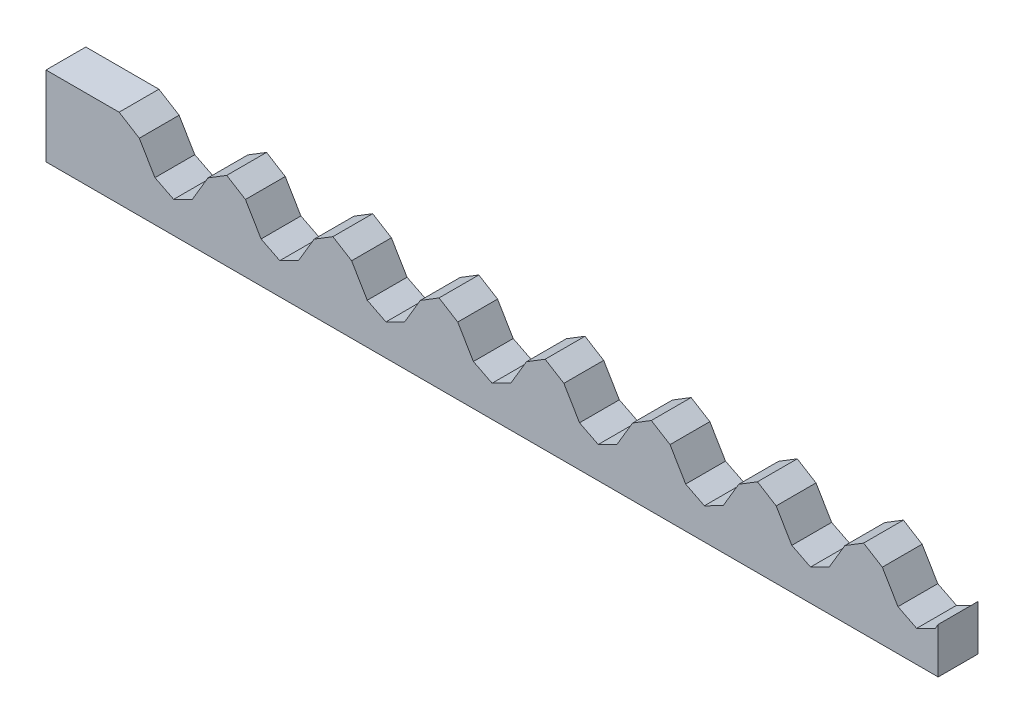
SolidWorks part; units mm, degrees
ref_plane "Front Plane" through (0, 0, 0) normal (0, 0, 1) x (1, 0, 0)
ref_plane "Top Plane" through (0, 0, 0) normal (0, 1, 0) x (1, 0, 0)
ref_plane "Right Plane" through (0, 0, 0) normal (1, 0, 0) x (0, 0, -1)
sketch "Sketch1" plane through (0, 0, 0) normal (0, 0, 1) x (1, 0, 0)
  line L1 (33.6217, -3) -> (-33.6217, -3)
  line L2 (33.6217, -3) -> (33.6217, 3)
  line L3 (33.6217, 3) -> (-33.6217, 3)
  line L4 (-33.6217, -3) -> (-33.6217, 3)
  point P4 (33.6217, 0)
  point P6 (0, 3)
  dimension "D1" = 6
extrude "Boss-Extrude1" add sketch "Sketch1" along normal blind 3
sketch "Sketch2" plane through (0, 0, 0) normal (0, 0, 1) x (1, 0, 0)
  line L0 (0, 3.9358) -> (0, 0.6556) construction
  line L1 (0, -0.6345) -> (-1.4103, 0.0759)
  line L2 (-1.4103, 0.0759) -> (-2.5892, 2.0635)
  line L3 (-2.5892, 2.0635) -> (-4.1115, 3)
  line L4 (-4.1115, 3) -> (-4.9816, 3.9358)
  line L5 (-4.9816, 3.9358) -> (0, 4.8886)
  line L6 (4.9816, 3.9358) -> (0, 4.8886)
  line L7 (4.1115, 3) -> (4.9816, 3.9358)
  line L8 (2.5892, 2.0635) -> (4.1115, 3)
  line L9 (1.4103, 0.0759) -> (2.5892, 2.0635)
  line L10 (0, -0.6345) -> (1.4103, 0.0759)
  line L11 (33.6217, 3) -> (-33.6217, 3) construction
extrude "Cut-Extrude1" cut sketch "Sketch2" along normal through all both and the other way through all
pattern_linear "LPattern1" count 4 spacing 8 along (-1, 0, 0) count 6 spacing 8 along (1, 0, 0) of "Cut-Extrude1"
